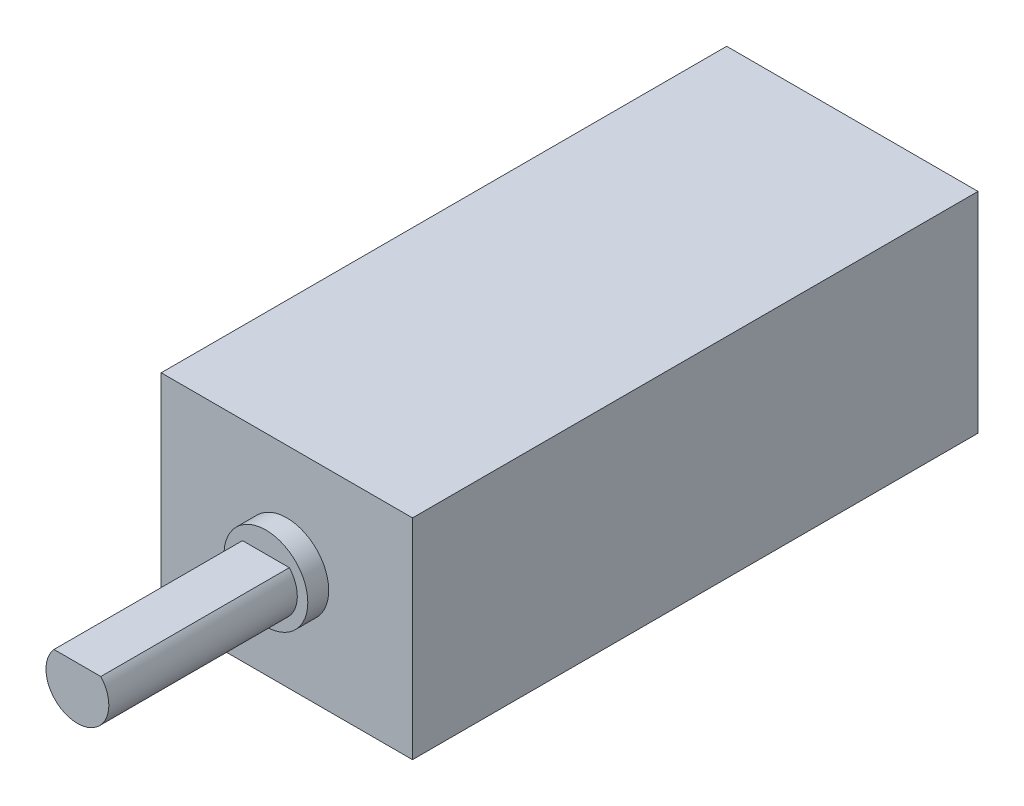
SolidWorks part; units mm, degrees
ref_plane "Front Plane" through (0, 0, 0) normal (0, 0, 1) x (1, 0, 0)
ref_plane "Top Plane" through (0, 0, 0) normal (0, 1, 0) x (1, 0, 0)
ref_plane "Right Plane" through (0, 0, 0) normal (1, 0, 0) x (0, 0, -1)
sketch "Sketch2" plane through (0, 0, 0) normal (0, 1, 0) x (1, 0, 0)
  line L1 (-6, 13.5) -> (6, 13.5)
  line L2 (-6, 13.5) -> (-6, -13.5)
  line L3 (-6, -13.5) -> (6, -13.5)
  line L4 (6, 13.5) -> (6, -13.5)
  line L5 (-6, 13.5) -> (6, -13.5) construction
  line L6 (-6, -13.5) -> (6, 13.5) construction
  point P0 (0, 0)
  dimension "D1" = 27
  dimension "D2" = 12
extrude "Boss-Extrude1" add sketch "Sketch2" along normal blind 10
sketch "Sketch4" plane through (0, 0, 13.5) normal (0, 0, 1) x (1, 0, 0)
  line L0 (-6, 10) -> (6, 0) construction
  line L1 (6, 10) -> (-6, 0) construction
  circle A0 centre (0, 5) radius 2
  dimension "D1" = 4
extrude "Boss-Extrude2" add sketch "Sketch4" along normal blind 1
sketch "Sketch5" plane through (0, 0, 14.5) normal (0, 0, 1) x (1, 0, 0)
  line L0 (-1.118, 6) -> (1.118, 6)
  arc A0 (-1.118, 6) -> (1.118, 6) centre (0, 5) ccw
  dimension "D1" = 3
  dimension "D2" = 1
extrude "Boss-Extrude3" add sketch "Sketch5" along normal blind 9
equation "\"D2@Sketch5\"=2.5-1.5"
